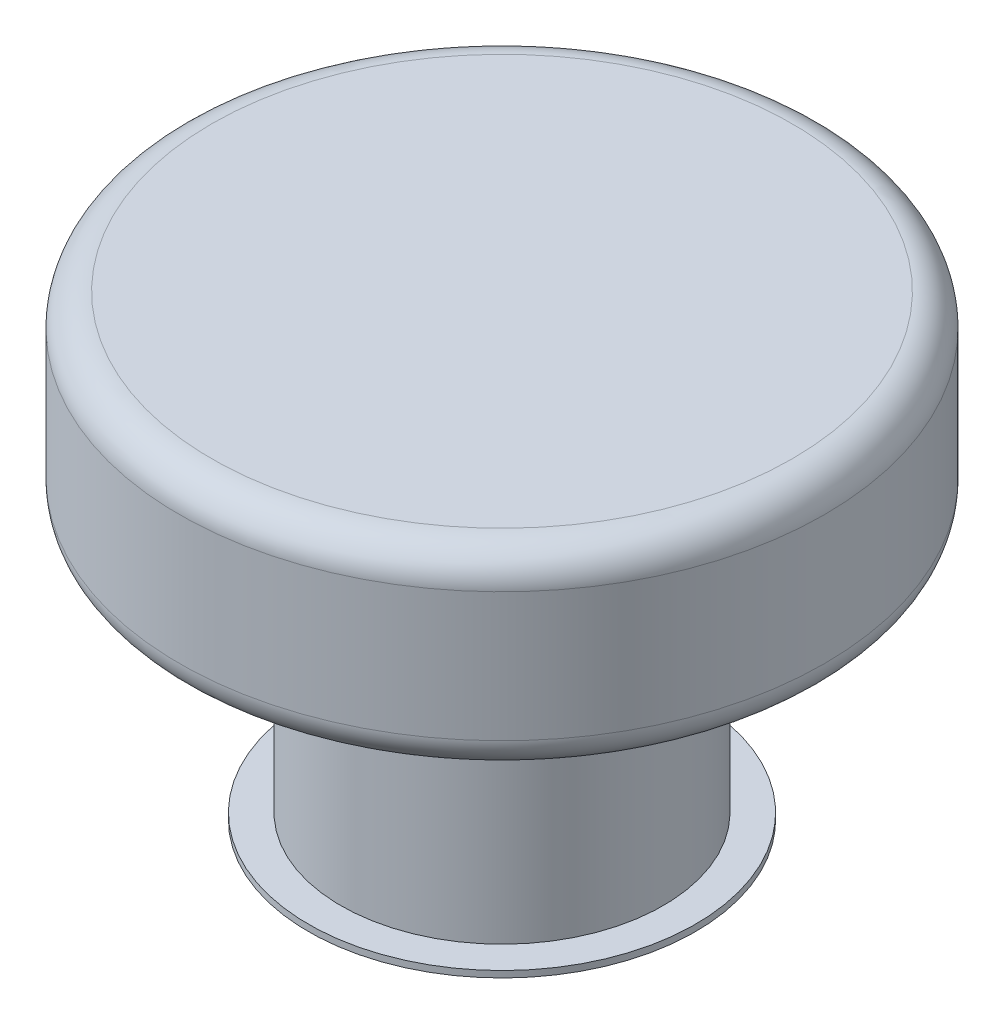
SolidWorks part; units mm, degrees
ref_plane "Front Plane" through (0, 0, 0) normal (0, 0, 1) x (1, 0, 0)
ref_plane "Top Plane" through (0, 0, 0) normal (0, 1, 0) x (1, 0, 0)
ref_plane "Right Plane" through (0, 0, 0) normal (1, 0, 0) x (0, 0, -1)
sketch "Sketch1" plane through (0, 0, 0) normal (0, 0, 1) x (1, 0, 0)
  line L0 (0, 0) -> (0.25, 0)
  line L1 (0.25, 0) -> (0.25, 0.4)
  line L2 (0.25, 0.4) -> (0.5, 0.4)
  line L3 (0.5, 0.4) -> (0.5, 0.7)
  line L4 (0.5, 0.7) -> (0, 0.7)
  line L5 (0, 0.7) -> (0, 0)
  dimension "D1" = 0.25
  dimension "D2" = 0.4
  dimension "D3" = 0.5
  dimension "D4" = 0.3
revolve "Revolve1" add sketch "Sketch1" angle 360 about L5
fillet "Fillet1" radius 0.05 2 edges at (-0.5, 0.4, 0) (-0.5, 0.7, 0)
sketch "Sketch2" plane through (0, 0, 0) normal (0, -1, 0) x (-1, 0, 0)
  circle A0 centre (0, 0) radius 0.3
  dimension "D1" = 0.6
extrude "Boss-Extrude1" add sketch "Sketch2" along normal blind 0.01
